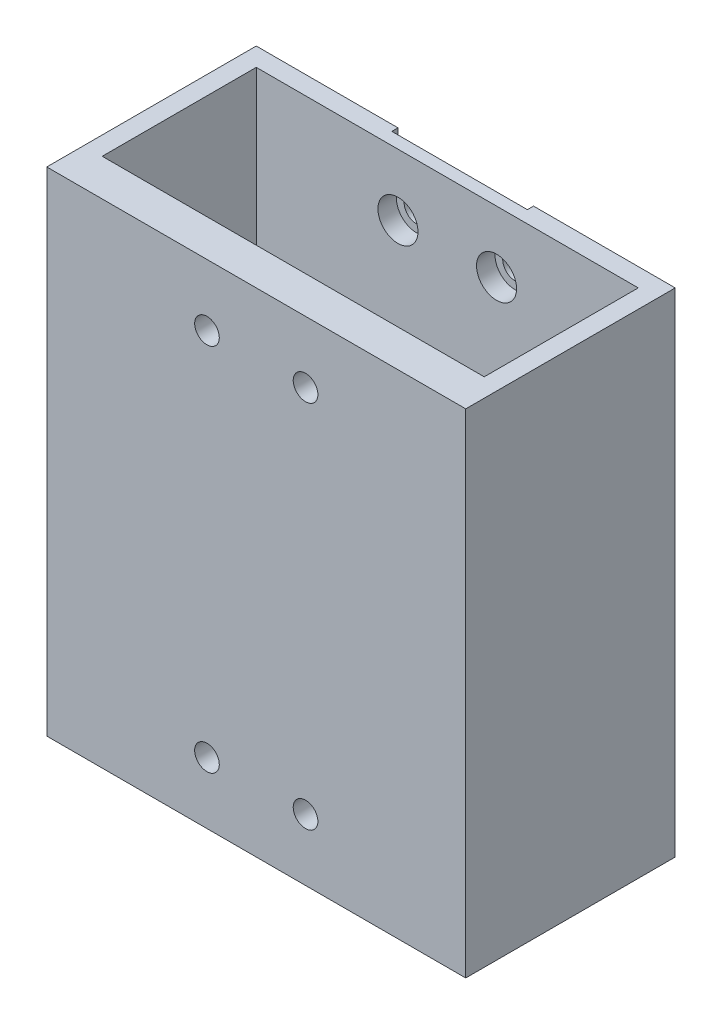
SolidWorks part; units mm, degrees
ref_plane "前视基准面" through (0, 0, 0) normal (0, 0, 1) x (1, 0, 0)
ref_plane "上视基准面" through (0, 0, 0) normal (0, 1, 0) x (1, 0, 0)
ref_plane "右视基准面" through (0, 0, 0) normal (1, 0, 0) x (0, 0, -1)
sketch "草图1" plane through (0, 0, 0) normal (0, 1, 0) x (1, 0, 0)
  line L1 (-31, 12.5) -> (31, 12.5)
  line L2 (-31, 12.5) -> (-31, -12.5)
  line L3 (-31, -12.5) -> (31, -12.5)
  line L4 (31, 12.5) -> (31, -12.5)
  line L5 (0, -12.5) -> (0, 12.5) construction
  line L6 (-31, 0) -> (31, 0) construction
  line L7 (-34, 15.5) -> (34, 15.5)
  line L8 (-34, 15.5) -> (-34, -15.5)
  line L9 (-34, -15.5) -> (34, -15.5)
  line L10 (34, 15.5) -> (34, -15.5)
  line L11 (0, -15.5) -> (0, 15.5) construction
  line L12 (-34, 0) -> (34, 0) construction
  point P0 (0, 0)
  point P4 (0, 0)
  dimension "D1" = 25
  dimension "D2" = 62
  dimension "D3" = 3
  dimension "D4" = 3
extrude "凸台-拉伸1" add sketch "草图1" along normal blind 20
sketch "草图2" plane through (0, 20, 0) normal (0, 1, 0) x (1, 0, 0)
  line L0 (34, -15.5) -> (34, 15.5) construction
  line L1 (-34, 15.5) -> (34, 15.5) construction
  line L2 (-34, 15.5) -> (-34, 12.5) construction
  line L3 (-34, 12.5) -> (34, 12.5) construction
  line L4 (34, 15.5) -> (34, 12.5) construction
  line L5 (0, 12.5) -> (0, 15.5) construction
  line L6 (-34, 14) -> (34, 14) construction
  line L8 (-11, 15.5) -> (11, 15.5) construction
  line L9 (-11, 15.5) -> (-11, 12.5) construction
  line L10 (-11, 12.5) -> (11, 12.5) construction
  line L11 (11, 15.5) -> (11, 12.5) construction
  line L12 (0, 12.5) -> (0, 15.5) construction
  line L13 (-11, 14) -> (11, 14) construction
  line L14 (-11, 15.5) -> (11, 15.5)
  line L15 (-11, 15.5) -> (-11, 14.5)
  line L16 (-11, 14.5) -> (11, 14.5)
  line L17 (11, 15.5) -> (11, 14.5)
  line L18 (0, 14.5) -> (0, 15.5) construction
  line L19 (-11, 15) -> (11, 15) construction
  point P6 (0, 14)
  point P125 (0, 15)
  point P180 (0, 14)
  dimension "D1" = 3
  dimension "D2" = 22
  dimension "D3" = 1
extrude "切除-拉伸1" cut sketch "草图2" against normal blind 6
sketch "草图3" plane through (0, 0, -15.5) normal (0, 0, -1) x (-1, 0, 0)
  line L0 (11, 14) -> (-11, 14) construction
  line L1 (-34, 20) -> (34, 20) construction
  line L2 (-34, 20) -> (-34, 0) construction
  line L3 (-34, 0) -> (34, 0) construction
  line L4 (34, 20) -> (34, 0) construction
  line L5 (0, 0) -> (0, 20) construction
  line L6 (-34, 10) -> (34, 10) construction
  line L7 (-11, 20) -> (11, 20) construction
  line L8 (-11, 20) -> (-11, 14) construction
  line L9 (-11, 14) -> (11, 14) construction
  line L10 (11, 20) -> (11, 14) construction
  line L11 (0, 14) -> (0, 20) construction
  line L12 (-11, 17) -> (11, 17) construction
  line L13 (-11, 14) -> (11, 14) construction
  line L14 (-8, 10) -> (8, 10) construction
  line L15 (-11, 20) -> (11, 20) construction
  line L16 (-11, 20) -> (-11, 15) construction
  line L17 (-11, 15) -> (11, 15) construction
  line L18 (11, 20) -> (11, 15) construction
  line L19 (0, 15) -> (0, 20) construction
  line L20 (-11, 17.5) -> (11, 17.5) construction
  line L21 (-11, 15) -> (11, 15) construction
  line L22 (-11, 15) -> (-11, 10) construction
  line L23 (-11, 10) -> (11, 10) construction
  line L24 (11, 15) -> (11, 10) construction
  line L25 (0, 10) -> (0, 15) construction
  line L26 (-11, 12.5) -> (11, 12.5) construction
  circle A0 centre (-8, 10) radius 2
  circle A1 centre (8, 10) radius 2
  point P20 (0, 10)
  point P120 (0, 17)
  point P123 (0, 17.5)
  point P184 (0, 10)
  point P197 (0, 12.5)
  dimension "D1" = 5
  dimension "D2" = 5
  dimension "D3" = 16
extrude "切除-拉伸2" cut sketch "草图3" against normal up to surface (3 mm away) up to face at (0, 10, -12.5)
sketch "草图4" plane through (0, 0, -15.5) normal (0, 0, -1) x (-1, 0, 0)
  line L0 (-11, 14) -> (-13, 14)
  line L1 (-11, 14) -> (11, 14)
  line L3 (-11, 4) -> (11, 4)
  line L5 (0, 4) -> (0, 14) construction
  line L6 (-11, 9) -> (11, 9) construction
  line L7 (-11, 14) -> (-13, 14) construction
  line L8 (-11, 14) -> (-11, 4) construction
  line L9 (-11, 4) -> (-13, 4) construction
  line L10 (-13, 14) -> (-13, 4) construction
  line L11 (-12, 4) -> (-12, 14) construction
  line L12 (-11, 9) -> (-13, 9) construction
  line L13 (11, 14) -> (13, 14) construction
  line L14 (11, 14) -> (11, 4) construction
  line L15 (11, 4) -> (13, 4) construction
  line L16 (13, 14) -> (13, 4) construction
  line L17 (12, 4) -> (12, 14) construction
  line L18 (11, 9) -> (13, 9) construction
  line L19 (-13, 14) -> (-13, 4)
  line L20 (-13, 4) -> (-11, 4)
  line L21 (11, 14) -> (13, 14)
  line L22 (13, 14) -> (13, 4)
  line L23 (13, 4) -> (11, 4)
  point P133 (12, 9)
  point P172 (0, 9)
  point P304 (-12, 9)
  dimension "D1" = 10
  dimension "D2" = 22
  dimension "D3" = 2
  dimension "D4" = 2
extrude "凸台-拉伸2" add sketch "草图4" along normal blind 3
sketch "草图6" plane through (0, 0, -12.5) normal (0, 0, 1) x (1, 0, 0)
  circle A0 centre (-8, 10) radius 2
  circle A1 centre (8, 10) radius 2
extrude "切除-拉伸3" cut sketch "草图6" against normal through all both and the other way through all
sketch "草图8" plane through (0, 0, -12.5) normal (0, 0, 1) x (1, 0, 0)
  circle A0 centre (-8, 10) radius 3.25
  circle A1 centre (8, 10) radius 3.25
  dimension "D1" = 6.5
  dimension "D2" = 6.5
extrude "切除-拉伸6" cut sketch "草图8" against normal blind 3
sketch "草图9" plane through (0, 0, 0) normal (0, -1, 0) x (1, 0, 0)
  line L1 (-34, 15.5) -> (34, 15.5)
  line L2 (-34, 15.5) -> (-34, -15.5)
  line L3 (-34, -15.5) -> (34, -15.5)
  line L4 (34, 15.5) -> (34, -15.5)
  line L5 (0, -15.5) -> (0, 15.5) construction
  line L6 (-34, 0) -> (34, 0) construction
  line L7 (-31, 12.5) -> (31, 12.5)
  line L8 (-31, 12.5) -> (-31, -12.5)
  line L9 (-31, -12.5) -> (31, -12.5)
  line L10 (31, 12.5) -> (31, -12.5)
  line L11 (0, -12.5) -> (0, 12.5) construction
  line L12 (-31, 0) -> (31, 0) construction
  point P224 (0, 0)
  point P252 (0, 0)
extrude "凸台-拉伸3" add sketch "草图9" along normal blind 60
sketch "草图11" plane through (0, 0, 15.5) normal (0, 0, 1) x (1, 0, 0)
  line L1 (-34, 20) -> (34, 20)
  line L2 (-34, 20) -> (-34, -60)
  line L3 (-34, -60) -> (34, -60)
  line L4 (34, 20) -> (34, -60)
  line L5 (0, -60) -> (0, 20) construction
  line L6 (-34, -20) -> (34, -20) construction
  circle A0 centre (-8, 10) radius 2
  circle A1 centre (8, 10) radius 2
  point P284 (0, -20)
extrude "凸台-拉伸5" add sketch "草图11" along normal blind 3
sketch "草图12" plane through (0, 0, 12.5) normal (0, 0, -1) x (-1, 0, 0)
  circle A0 centre (-8, 10) radius 6
  circle A1 centre (8, 10) radius 6
extrude "切除-拉伸7" cut sketch "草图12" against normal blind 3
ref_plane "基准面1" through (0, -20, 0) normal (0, 1, 0) x (1, 0, 0)
mirror "镜向1" about plane through (0, -20, 0) normal (0, 1, 0) of "切除-拉伸3", "切除-拉伸7"
